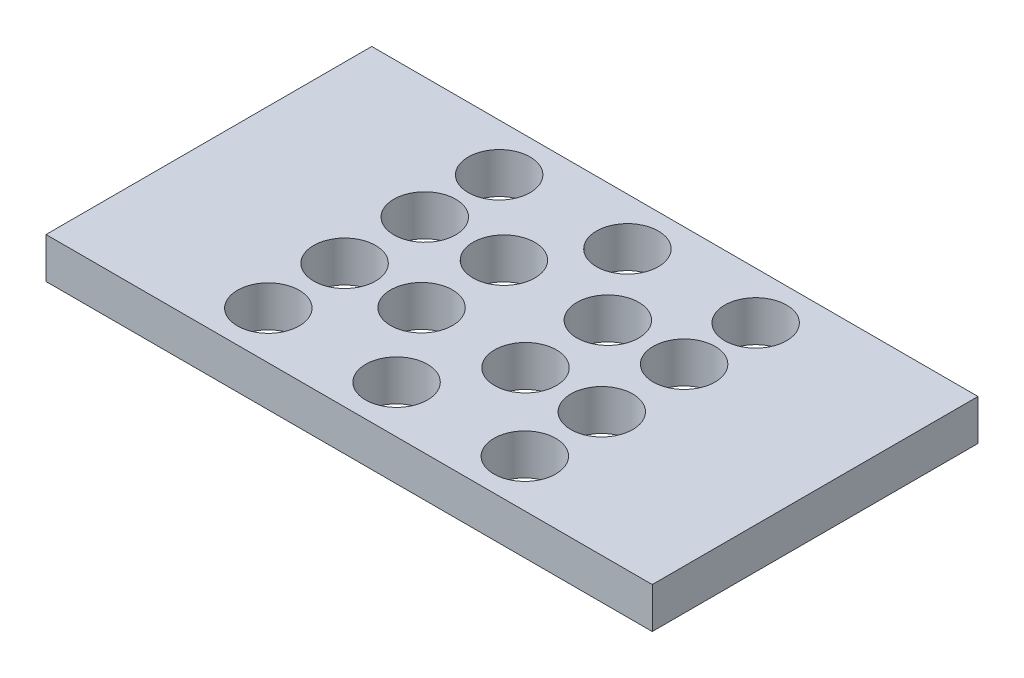
SolidWorks part; units mm, degrees
ref_plane "Front Plane" through (0, 0, 0) normal (0, 0, 1) x (1, 0, 0)
ref_plane "Top Plane" through (0, 0, 0) normal (0, 1, 0) x (1, 0, 0)
ref_plane "Right Plane" through (0, 0, 0) normal (1, 0, 0) x (0, 0, -1)
sketch "Sketch1" plane through (0, 0, 0) normal (0, 1, 0) x (1, 0, 0)
  line L3 (0, 18) -> (0, 6) construction
  line L5 (-47.2724, -25.4) -> (-47.2724, 25.4)
  line L7 (47.2724, -25.4) -> (47.2724, 25.4)
  line L8 (0, 6) -> (0, -6) construction
  line L9 (0, -6) -> (0, -18) construction
  line L10 (-47.2724, 25.4) -> (47.2724, 25.4)
  line L11 (47.2724, -25.4) -> (-47.2724, -25.4)
  line L16 (-8.1045, 6.844) -> (8.1045, 6.844) construction
  line L18 (-67.2724, 25.4) -> (27.2724, 25.4) [skipped]
  line L19 (27.2724, -25.4) -> (-67.2724, -25.4) [skipped]
  line L20 (67.2724, -25.4) -> (-27.2724, -25.4) [skipped]
  line L21 (-27.2724, 25.4) -> (67.2724, 25.4) [skipped]
  circle A1 centre (0, 18) radius 4.825
  circle A16 centre (0, -18) radius 4.825
  circle A17 centre (20, 18) radius 4.825
  circle A18 centre (20, 6.844) radius 4.825
  circle A19 centre (20, -6) radius 4.825
  circle A20 centre (20, -18) radius 4.825
  circle A21 centre (-20, 18) radius 4.825
  circle A22 centre (-20.0995, 6.4968) radius 4.825
  circle A23 centre (-20.1045, -6) radius 4.825
  circle A24 centre (-20, -18) radius 4.825
  circle A25 centre (-8.1045, 6.844) radius 4.825
  circle A26 centre (-8.1045, -6) radius 4.825
  circle A27 centre (8.1045, 6.844) radius 4.825
  circle A28 centre (8.1045, -6) radius 4.825
  point P0 (0, 0)
  point P13 (0, 0)
  point P27 (0, 0)
  point P35 (0, 0)
  point P46 (0, 6.844)
  point P49 (0, 0)
  point P50 (0, 0)
  dimension "D1" = 9.65
  dimension "D2" = 50.8
  dimension "D7" = 2
  dimension "D5" = 2
  dimension "D6" = 12
  dimension "D3" = 12
  dimension "D4" = 2
extrude "Boss-Extrude1" add sketch "Sketch1" along normal blind 6.35
